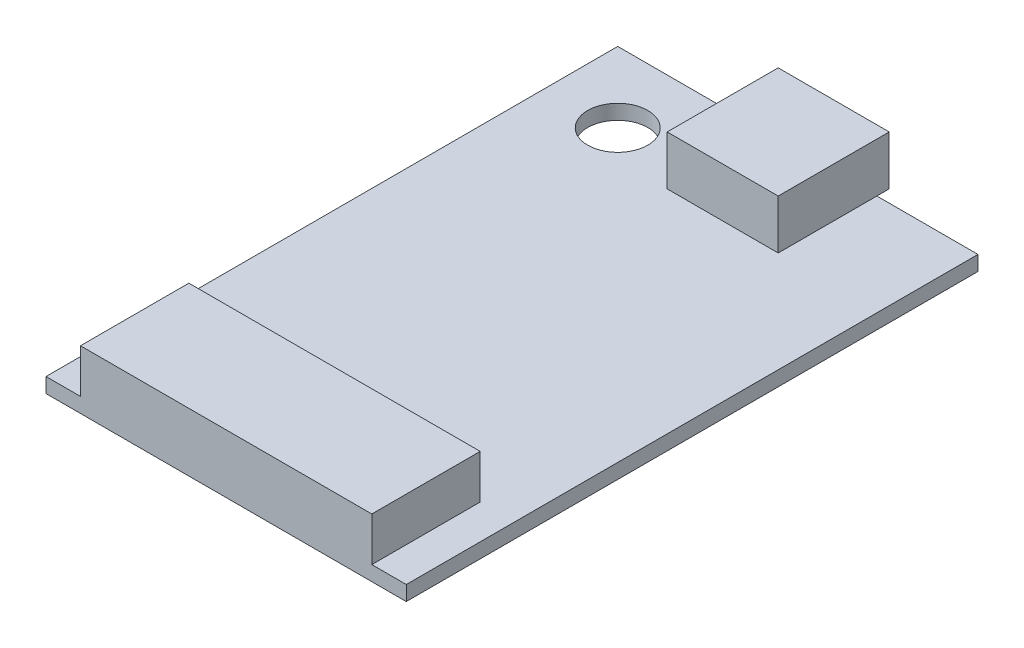
SolidWorks part; units mm, degrees
ref_plane "Front Plane" through (0, 0, 0) normal (0, 0, 1) x (1, 0, 0)
ref_plane "Top Plane" through (0, 0, 0) normal (0, 1, 0) x (1, 0, 0)
ref_plane "Right Plane" through (0, 0, 0) normal (1, 0, 0) x (0, 0, -1)
sketch "Sketch1" plane through (0, 0, 0) normal (0, 1, 0) x (1, 0, 0)
  line L1 (-7.3025, -11.5888) -> (7.3025, -11.5888)
  line L2 (-7.3025, -11.5888) -> (-7.3025, 11.5887)
  line L3 (-7.3025, 11.5887) -> (7.3025, 11.5887)
  line L4 (7.3025, -11.5888) -> (7.3025, 11.5887)
  line L5 (-7.3025, -11.5888) -> (7.3025, 11.5887) construction
  line L6 (-7.3025, 11.5887) -> (7.3025, -11.5888) construction
  point P0 (0, 0)
  dimension "D1" = 23.1775
  dimension "D2" = 14.605
extrude "Boss-Extrude1" add sketch "Sketch1" along normal blind 0.6
sketch "Sketch2" plane through (0, 0.6, 0) normal (0, 1, 0) x (1, 0, 0)
  line L0 (7.3025, 11.5887) -> (-7.3025, 11.5887) construction
  line L1 (7.3025, -11.5888) -> (7.3025, 11.5887) construction
  circle A0 centre (-4.445, 8.7312) radius 1.2192
  dimension "D3" = 2.4384
  dimension "D1" = 2.8575
  dimension "D2" = 11.7475
extrude "Cut-Extrude1" cut sketch "Sketch2" against normal through all
sketch "Sketch3" plane through (0, 0.6, 0.6) normal (0, 1, 0) x (1, 0, 0)
  line L1 (-5.9055, -6.5946) -> (5.9055, -6.5946)
  line L2 (-5.9055, -6.5946) -> (-5.9055, -10.9888)
  line L3 (-5.9055, -10.9888) -> (5.9055, -10.9888)
  line L4 (5.9055, -6.5946) -> (5.9055, -10.9888)
  line L5 (-5.9055, -6.5946) -> (5.9055, -10.9888) construction
  line L6 (-5.9055, -10.9888) -> (5.9055, -6.5946) construction
  line L7 (-7.3025, -10.9888) -> (7.3025, -10.9888) construction
  point P0 (0, -8.7917)
  point P7 (0, -10.9888)
  dimension "D1" = 11.811
  dimension "D2" = 4.3942
extrude "Boss-Extrude2" add sketch "Sketch3" along normal blind 1.778
sketch "Sketch4" plane through (0, 0.6, 0) normal (0, 1, 0) x (1, 0, 0)
  line L0 (7.3025, -11.5888) -> (7.3025, 11.5887) construction
  line L1 (3.2025, 7.5887) -> (-1.2975, 7.5887)
  line L2 (3.2025, 7.5887) -> (3.2025, 12.0887)
  line L3 (3.2025, 12.0887) -> (-1.2975, 12.0887)
  line L4 (-1.2975, 7.5887) -> (-1.2975, 12.0887)
  line L5 (3.2025, 7.5887) -> (-1.2975, 12.0887) construction
  line L6 (3.2025, 12.0887) -> (-1.2975, 7.5887) construction
  line L7 (7.3025, 11.5887) -> (-7.3025, 11.5887) construction
  point P0 (0.9525, 9.8387)
  dimension "D1" = 4.5
  dimension "D2" = 4.5
  dimension "D3" = 0.5
  dimension "D4" = 6.35
extrude "Boss-Extrude3" add sketch "Sketch4" along normal blind 2
